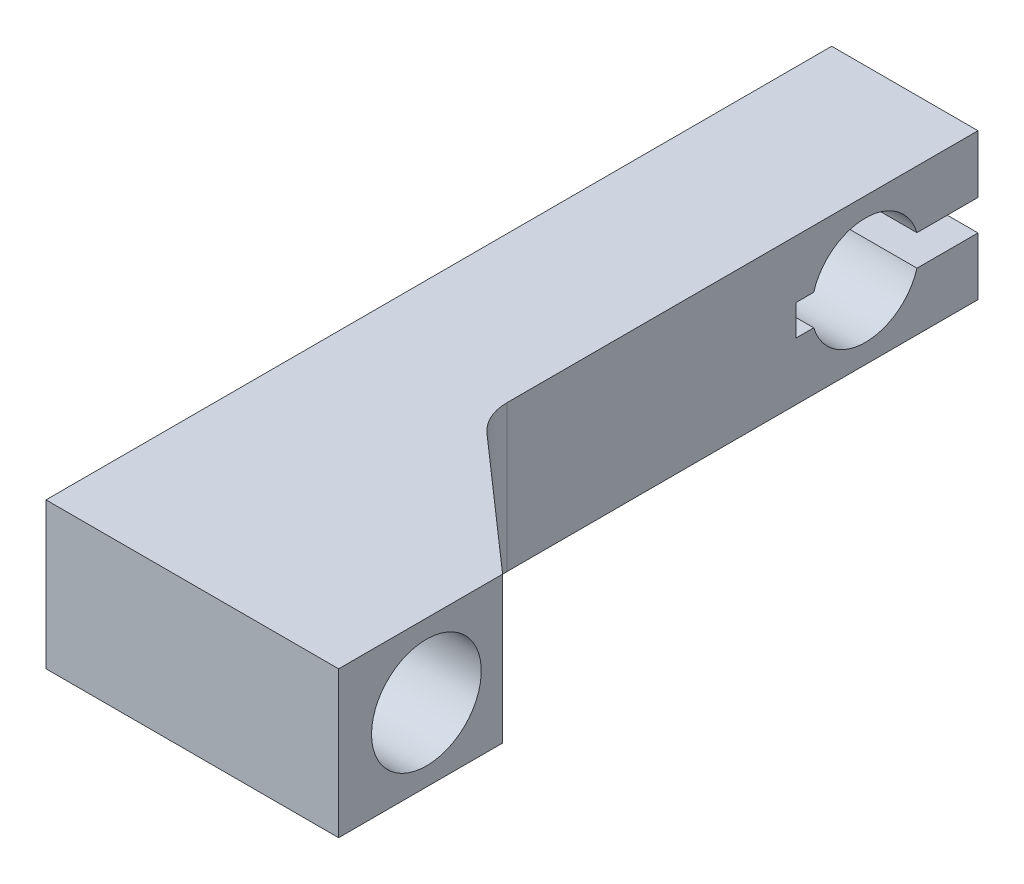
SolidWorks part; units mm, degrees
material "6061-T6 (SS)"
ref_plane "Front Plane" through (0, 0, 0) normal (0, 0, 1) x (1, 0, 0)
ref_plane "Top Plane" through (0, 0, 0) normal (0, 1, 0) x (1, 0, 0)
ref_plane "Right Plane" through (0, 0, 0) normal (1, 0, 0) x (0, 0, -1)
sketch "Sketch1" plane through (0, 0, 0) normal (1, 0, 0) x (0, 0, -1)
  line L0 (0, 0) -> (29.3372, 0) construction
  line L1 (29.3372, -19.05) -> (-175.2557, -19.05)
  line L2 (29.3372, -19.05) -> (29.3372, -4)
  line L3 (29.3372, 19.05) -> (-175.2557, 19.05)
  line L4 (-175.2557, -19.05) -> (-175.2557, 19.05)
  line L5 (-18.025, 0) -> (0, 0) construction
  line L6 (-18.025, 4) -> (-13.4425, 4)
  line L7 (-18.025, 4) -> (-18.025, -4)
  line L8 (-18.025, -4) -> (-13.4425, -4)
  line L10 (29.3372, 4) -> (29.3372, 19.05)
  line L11 (13.4425, 4) -> (29.3372, 4)
  line L12 (13.4425, -4) -> (29.3372, -4)
  line L13 (0, 0) -> (-152.4, 0) construction
  arc A0 (13.4425, 4) -> (-13.4425, 4) centre (0, 0) ccw
  arc A1 (-13.4425, -4) -> (13.4425, -4) centre (0, 0) ccw
  circle A2 centre (-152.4, 0) radius 14.2875
  point P13 (-14.025, 0)
  dimension "D1" = 28.05
  dimension "D6" = 28.575
  dimension "D2" = 8
  dimension "D3" = 4
  dimension "D4" = 38.1
  dimension "D5" = 152.4
extrude "Boss-Extrude1" add sketch "Sketch1" along normal blind 38.1
sketch "Sketch2" plane through (38.1, 0, 0) normal (1, 0, 0) x (0, 0, -1)
  line L0 (-175.2557, -19.05) -> (29.3372, -19.05) construction
  line L1 (-175.2557, 19.05) -> (-99.0557, 19.05)
  line L2 (-175.2557, 19.05) -> (-175.2557, -19.05)
  line L3 (-175.2557, -19.05) -> (-99.0557, -19.05)
  line L4 (-99.0557, 19.05) -> (-99.0557, -19.05)
  circle A0 centre (-152.4, 0) radius 14.2875 construction
  circle A1 centre (-152.4, 0) radius 14.2875
  dimension "D1" = 76.2
extrude "Boss-Extrude2" add sketch "Sketch2" along normal blind 38.1
sketch "Sketch3" plane through (0, 19.05, 0) normal (0, 1, 0) x (1, 0, 0)
  line L0 (38.1, -99.0557) -> (76.2, -132.5624)
  line L1 (76.2, -99.0557) -> (76.2, -175.2557) construction
  line L2 (38.1, -99.0557) -> (94.2773, -84.4492)
  line L3 (94.2773, -84.4492) -> (76.2, -132.5624)
extrude "Cut-Extrude1" cut sketch "Sketch3" against normal blind 38.1
fillet "Fillet1" radius 12.7 1 edges at (38.1, 0, 99.0557)
